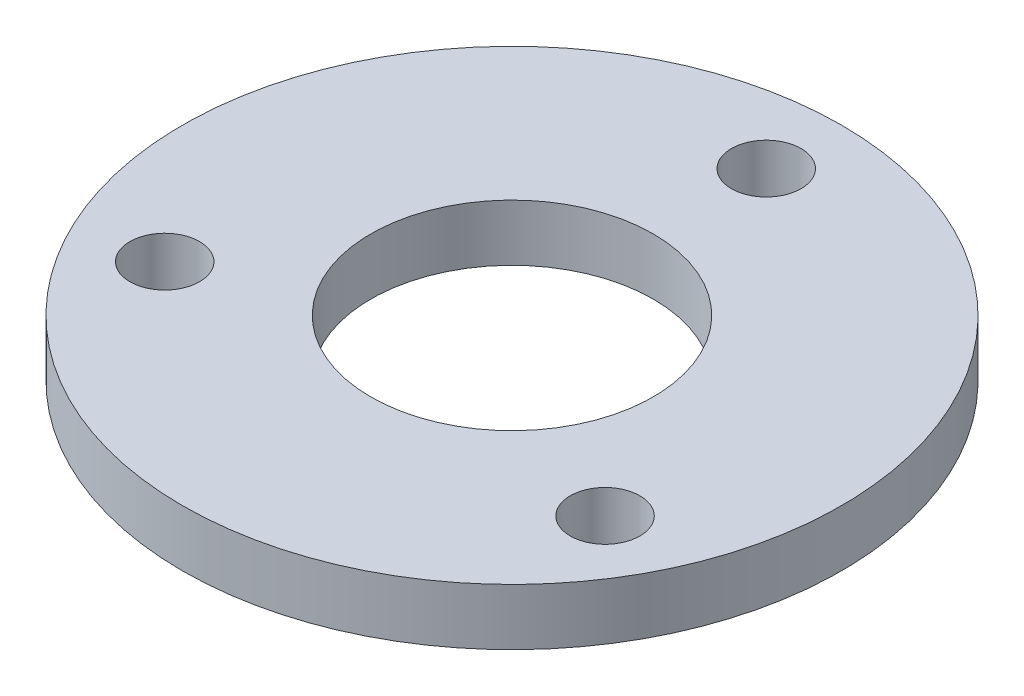
SolidWorks part; units mm, degrees
ref_plane "前视基准面" through (0, 0, 0) normal (0, 0, 1) x (1, 0, 0)
ref_plane "上视基准面" through (0, 0, 0) normal (0, 1, 0) x (1, 0, 0)
ref_plane "右视基准面" through (0, 0, 0) normal (1, 0, 0) x (0, 0, -1)
other "Configuration Table"
sketch "草图1" plane through (0, 0, 0) normal (0, 1, 0) x (1, 0, 0)
  circle A0 centre (0, 0) radius 13.5 construction
  circle A1 centre (0, 0) radius 17.5
  circle A2 centre (0, 13.5) radius 1.85
  circle A3 centre (11.6913, -6.75) radius 1.85
  circle A4 centre (-11.6913, -6.75) radius 1.85
  circle A5 centre (0, 0) radius 7.5
  point P12 (0, 0)
  dimension "D1" = 35
  dimension "D2" = 27
  dimension "D3" = 3.7
  dimension "D5" = 15
  dimension "D4" = 3
extrude "凸台-拉伸1" add sketch "草图1" along normal blind 3
